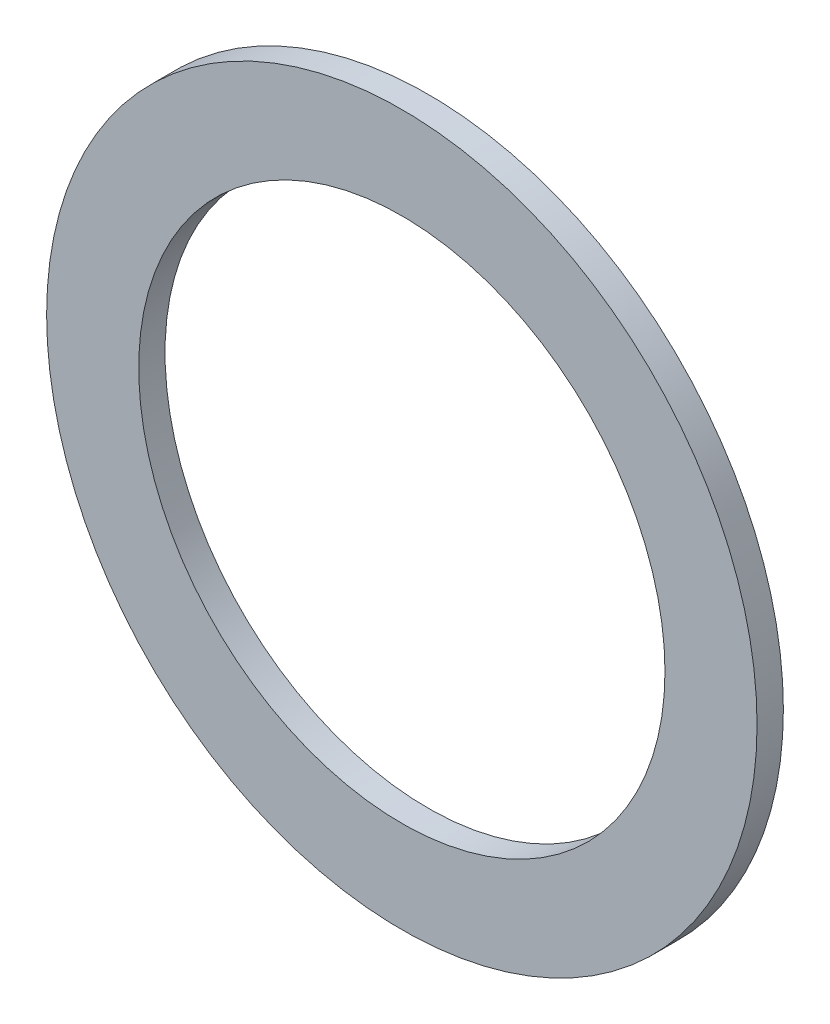
SolidWorks part; units mm, degrees
ref_plane "Front Plane" through (0, 0, 0) normal (0, 0, 1) x (1, 0, 0)
ref_plane "Top Plane" through (0, 0, 0) normal (0, 1, 0) x (1, 0, 0)
ref_plane "Right Plane" through (0, 0, 0) normal (1, 0, 0) x (0, 0, -1)
sketch "Sketch1" plane through (0, 0, 0) normal (0, 0, 1) x (1, 0, 0)
  circle A0 centre (0, 0) radius 10
  circle A1 centre (0, 0) radius 13.5
  dimension "D1" = 20
  dimension "D2" = 27
extrude "Boss-Extrude1" add sketch "Sketch1" along normal blind 1
